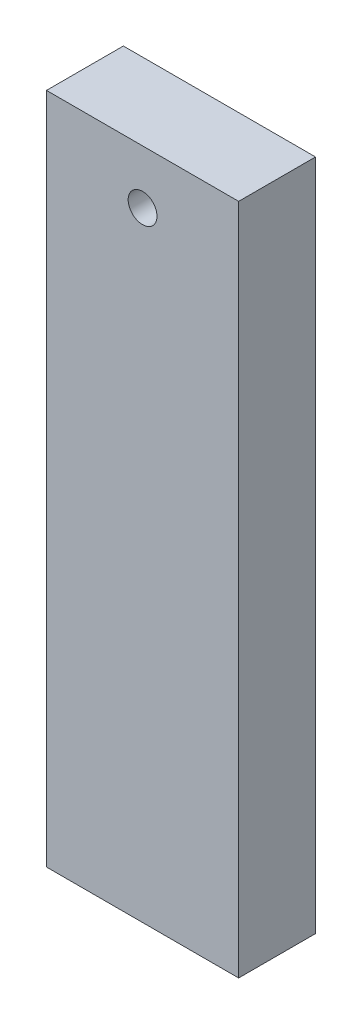
SolidWorks part; units mm, degrees
material "Oak"
ref_plane "Front Plane" through (0, 0, 0) normal (0, 0, 1) x (1, 0, 0)
ref_plane "Top Plane" through (0, 0, 0) normal (0, 1, 0) x (1, 0, 0)
ref_plane "Right Plane" through (0, 0, 0) normal (1, 0, 0) x (0, 0, -1)
sketch "Sketch1" plane through (0, 0, 0) normal (0, 1, 0) x (1, 0, 0)
  line L1 (-25.4, 10.16) -> (25.4, 10.16)
  line L2 (-25.4, 10.16) -> (-25.4, -10.16)
  line L3 (-25.4, -10.16) -> (25.4, -10.16)
  line L4 (25.4, 10.16) -> (25.4, -10.16)
  line L5 (-25.4, 10.16) -> (25.4, -10.16) construction
  line L6 (-25.4, -10.16) -> (25.4, 10.16) construction
  point P0 (0, 0)
  dimension "D1" = 50.8
  dimension "D2" = 20.32
extrude "Boss-Extrude1" add sketch "Sketch1" along normal blind 177.8 contours L1 L4 L3 L2
sketch "Sketch2" plane through (0, 0, -10.16) normal (0, 0, -1) x (-1, 0, 0)
  line L0 (0, 0) -> (0, 163.576) construction
  circle A0 centre (0, 163.576) radius 3.81
  dimension "D2" = 7.62
  dimension "D1" = 163.576
extrude "Cut-Extrude1" cut sketch "Sketch2" against normal through all contours A0
